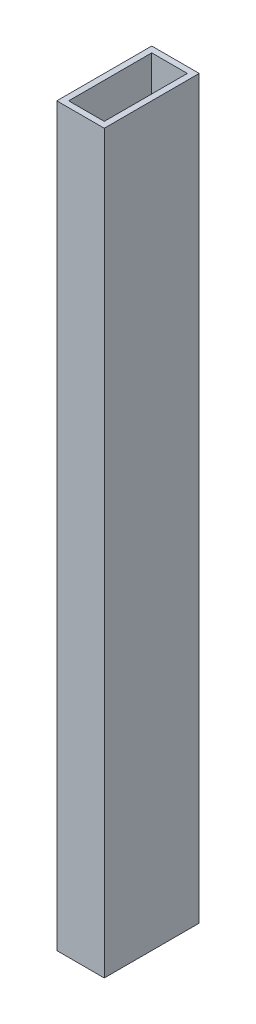
SolidWorks part; units mm, degrees
ref_plane "Front Plane" through (0, 0, 0) normal (0, 0, 1) x (1, 0, 0)
ref_plane "Top Plane" through (0, 0, 0) normal (0, 1, 0) x (1, 0, 0)
ref_plane "Right Plane" through (0, 0, 0) normal (1, 0, 0) x (0, 0, -1)
sketch "Sketch1" plane through (0, 0, 0) normal (0, 1, 0) x (1, 0, 0)
  line L0 (-9.525, 22.225) -> (9.525, 22.225)
  line L1 (-12.7, -25.4) -> (12.7, -25.4)
  line L2 (-12.7, -25.4) -> (-12.7, 25.4)
  line L3 (-12.7, 25.4) -> (12.7, 25.4)
  line L4 (12.7, -25.4) -> (12.7, 25.4)
  line L5 (-12.7, -25.4) -> (12.7, 25.4) construction
  line L6 (-12.7, 25.4) -> (12.7, -25.4) construction
  line L7 (9.525, -22.225) -> (9.525, 22.225)
  line L8 (-9.525, -22.225) -> (9.525, -22.225)
  line L9 (-9.525, -22.225) -> (-9.525, 22.225)
  point P0 (0, 0)
  dimension "D1" = 25.4
  dimension "D2" = 50.8
  dimension "D3" = 3.175
extrude "Boss-Extrude1" add sketch "Sketch1" along normal blind 393.7
